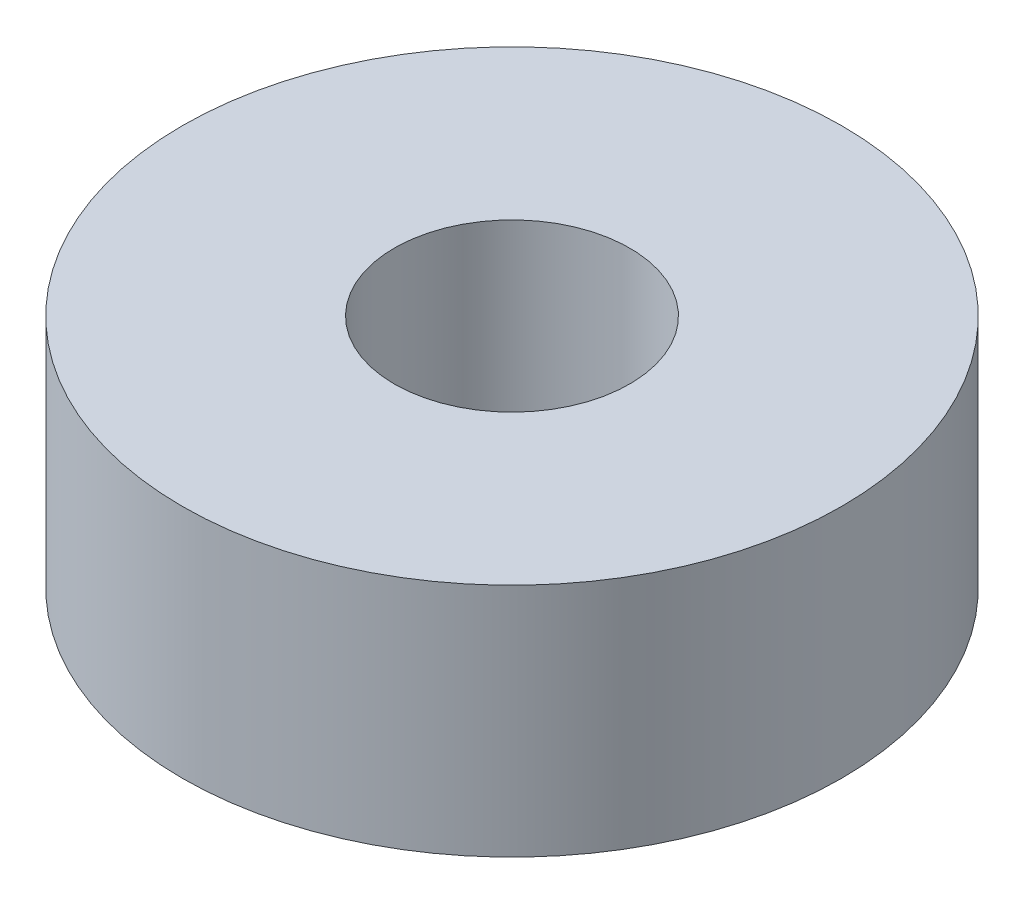
SolidWorks part; units mm, degrees
ref_plane "Front Plane" through (0, 0, 0) normal (0, 0, 1) x (1, 0, 0)
ref_plane "Top Plane" through (0, 0, 0) normal (0, 1, 0) x (1, 0, 0)
ref_plane "Right Plane" through (0, 0, 0) normal (1, 0, 0) x (0, 0, -1)
other "Default"
sketch "Sketch1" plane through (0, 0, 0) normal (0, 1, 0) x (1, 0, 0)
  circle A0 centre (0, 0) radius 2.5
  circle A1 centre (0, 0) radius 7
  dimension "ID" = 5
  dimension "OD" = 14
extrude "Boss-Extrude1" add sketch "Sketch1" along normal mid plane 5
